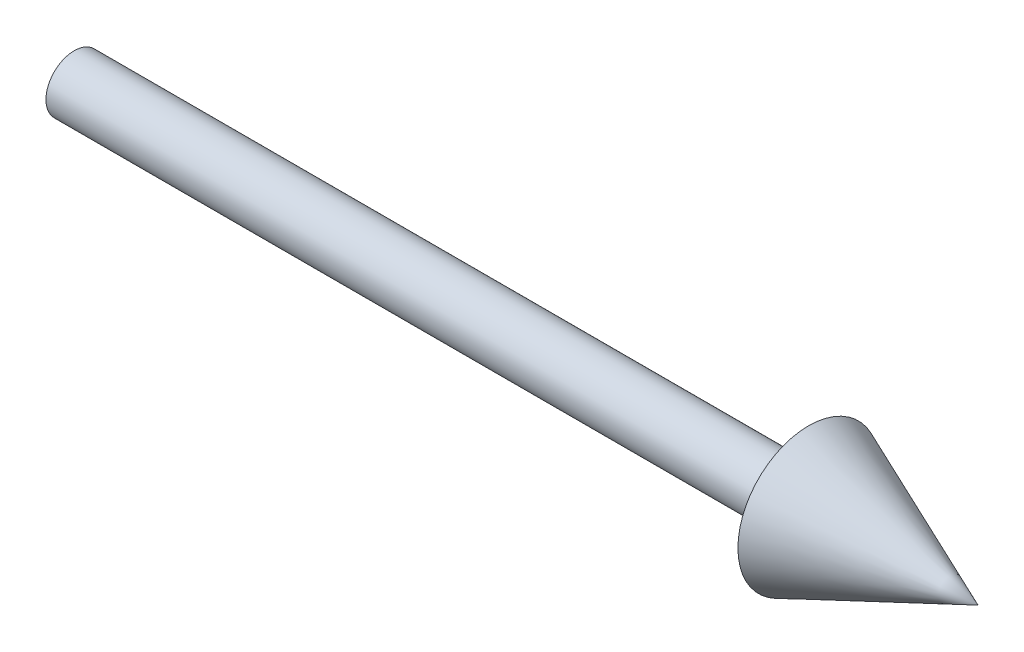
SolidWorks part; units mm, degrees
ref_plane "Front Plane" through (0, 0, 0) normal (0, 0, 1) x (1, 0, 0)
ref_plane "Top Plane" through (0, 0, 0) normal (0, 1, 0) x (1, 0, 0)
ref_plane "Right Plane" through (0, 0, 0) normal (1, 0, 0) x (0, 0, -1)
sketch "Sketch1" plane through (0, 0, 0) normal (0, 0, 1) x (1, 0, 0)
  line L0 (0, 0) -> (-10.2712, 0) construction
  line L1 (0, 0) -> (0, 5)
  line L2 (0, 5) -> (130, 5)
  line L3 (130, 5) -> (130, 12.5)
  line L4 (130, 12.5) -> (160, 0)
  line L5 (160, 0) -> (0, 0)
  dimension "D1" = 160
  dimension "D2" = 10
  dimension "D3" = 30
  dimension "D4" = 25
revolve "Revolve1" add sketch "Sketch1" angle 360 about L0
